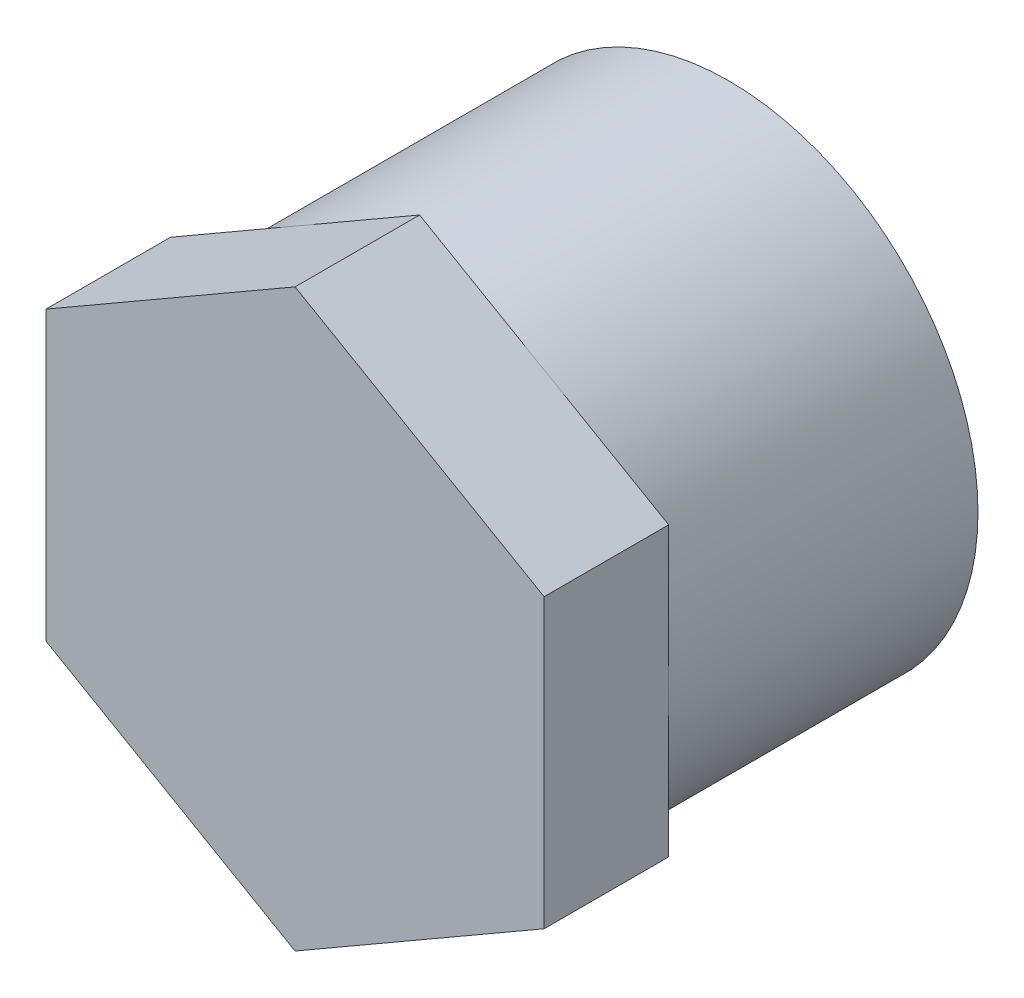
SolidWorks part; units mm, degrees
ref_plane "Front Plane" through (0, 0, 0) normal (0, 0, 1) x (1, 0, 0)
ref_plane "Top Plane" through (0, 0, 0) normal (0, 1, 0) x (1, 0, 0)
ref_plane "Right Plane" through (0, 0, 0) normal (1, 0, 0) x (0, 0, -1)
sketch "Sketch1" plane through (0, 0, 0) normal (0, 0, 1) x (1, 0, 0)
  circle A0 centre (0, 0) radius 10
extrude "Boss-Extrude1" add sketch "Sketch1" along normal blind 5 and the other way blind 7.42
sketch "Sketch2" plane through (0, 0, 5) normal (0, 0, 1) x (1, 0, 0)
  line L1 (0, 11.547) -> (-10, 5.7735)
  line L2 (-10, 5.7735) -> (-10, -5.7735)
  line L3 (-10, -5.7735) -> (0, -11.547)
  line L4 (0, -11.547) -> (10, -5.7735)
  line L5 (10, -5.7735) -> (10, 5.7735)
  line L6 (10, 5.7735) -> (0, 11.547)
  circle A0 centre (0, 0) radius 10 construction
  circle A1 centre (0, 0) radius 10 construction
extrude "Boss-Extrude2" add sketch "Sketch2" along normal blind 5
